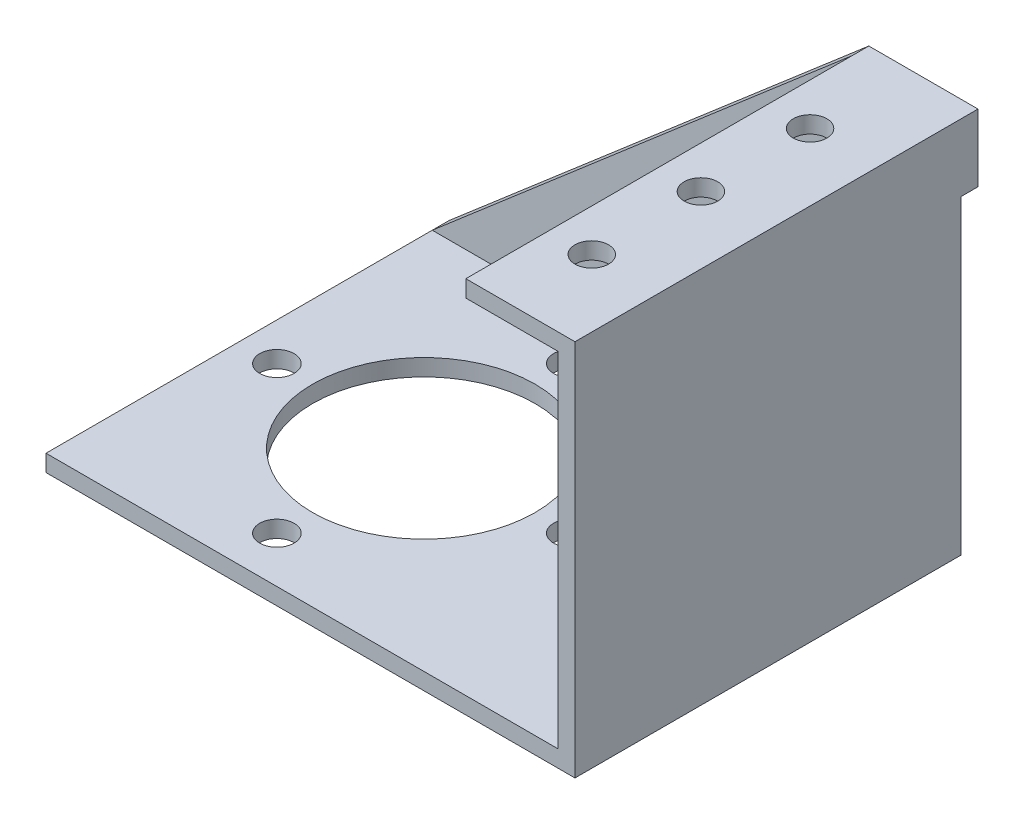
SolidWorks part; units mm, degrees
material "AISI 304"
ref_plane "前视基准面" through (0, 0, 0) normal (0, 0, 1) x (1, 0, 0)
ref_plane "上视基准面" through (0, 0, 0) normal (0, 1, 0) x (1, 0, 0)
ref_plane "右视基准面" through (0, 0, 0) normal (1, 0, 0) x (0, 0, -1)
sketch "Sketch1" plane through (0, 0, 0) normal (0, 0, 1) x (1, 0, 0)
  line L0 (0, 0) -> (0, 45)
  line L1 (0, 45) -> (-13, 45)
  line L2 (-13, 45) -> (-13, 43)
  line L3 (-13, 43) -> (-2, 43)
  line L4 (-2, 43) -> (-2, 2)
  line L5 (-2, 2) -> (-63, 2)
  line L6 (-63, 2) -> (-63, 0)
  line L7 (-63, 0) -> (0, 0)
  point P9 (-13, 44)
  dimension "D1" = 41
  dimension "D2" = 2
  dimension "D3" = 2
  dimension "D4" = 2
  dimension "D5" = 11
  dimension "D6" = 50
extrude "Boss-Extrude1" add sketch "Sketch1" along normal blind 46
sketch "Sketch2" plane through (0, 0, 0) normal (0, -1, 0) x (1, 0, 0)
  line L0 (-63, 23) -> (0, 23) construction
  line L1 (-63, 46) -> (-63, 0) construction
  line L2 (0, 46) -> (0, 0) construction
  line L3 (-41, 0) -> (-41, 46) construction
  line L4 (-63, 0) -> (0, 0) construction
  line L5 (-63, 46) -> (0, 46) construction
  circle A0 centre (-41, 23) radius 13.25
  circle A1 centre (-41, 23) radius 17.5 construction
  circle A2 centre (-41, 40.5) radius 2.05
  circle A3 centre (-58.5, 23) radius 2.05
  circle A4 centre (-23.5, 23) radius 2.05
  circle A5 centre (-41, 5.5) radius 2.05
  dimension "D2" = 4.1
  dimension "D3" = 4.1
  dimension "D4" = 4.1
  dimension "D5" = 4.1
  dimension "D6" = 35
  dimension "D7" = 26.5
  dimension "D1" = 22
extrude "Cut-Extrude1" cut sketch "Sketch2" against normal blind 2
sketch "Sketch3" plane through (0, 45, 0) normal (0, 1, 0) x (1, 0, 0)
  line L0 (-8, 0) -> (-8, -46) construction
  line L1 (0, 0) -> (-13, 0) construction
  line L2 (0, -46) -> (-13, -46) construction
  line L3 (-13, -46) -> (-13, 0) construction
  circle A0 centre (-8, -10) radius 2
  circle A1 centre (-8, -23) radius 2
  circle A2 centre (-8, -36) radius 2
  dimension "D2" = 4
  dimension "D3" = 4
  dimension "D4" = 4
  dimension "D6" = 10
  dimension "D7" = 13
  dimension "D1" = 5
  dimension "D5" = 10
extrude "Cut-Extrude2" cut sketch "Sketch3" against normal blind 100
sketch "Sketch4" plane through (0, 0, 0) normal (0, 0, -1) x (-1, 0, 0)
  line L0 (13, 45) -> (63, 2)
  line L1 (63, 2) -> (63, 0)
  line L8 (0, 45) -> (13, 45)
  line L9 (0, 45) -> (0, 36.98)
  line L10 (0, 0) -> (0, 45) construction
  line L11 (0, 36.98) -> (43, 0)
  line L12 (63, 0) -> (0, 0) construction
  line L13 (43, 0) -> (63, 0)
  dimension "D1" = 20
extrude "Boss-Extrude2" add sketch "Sketch4" along normal blind 2
